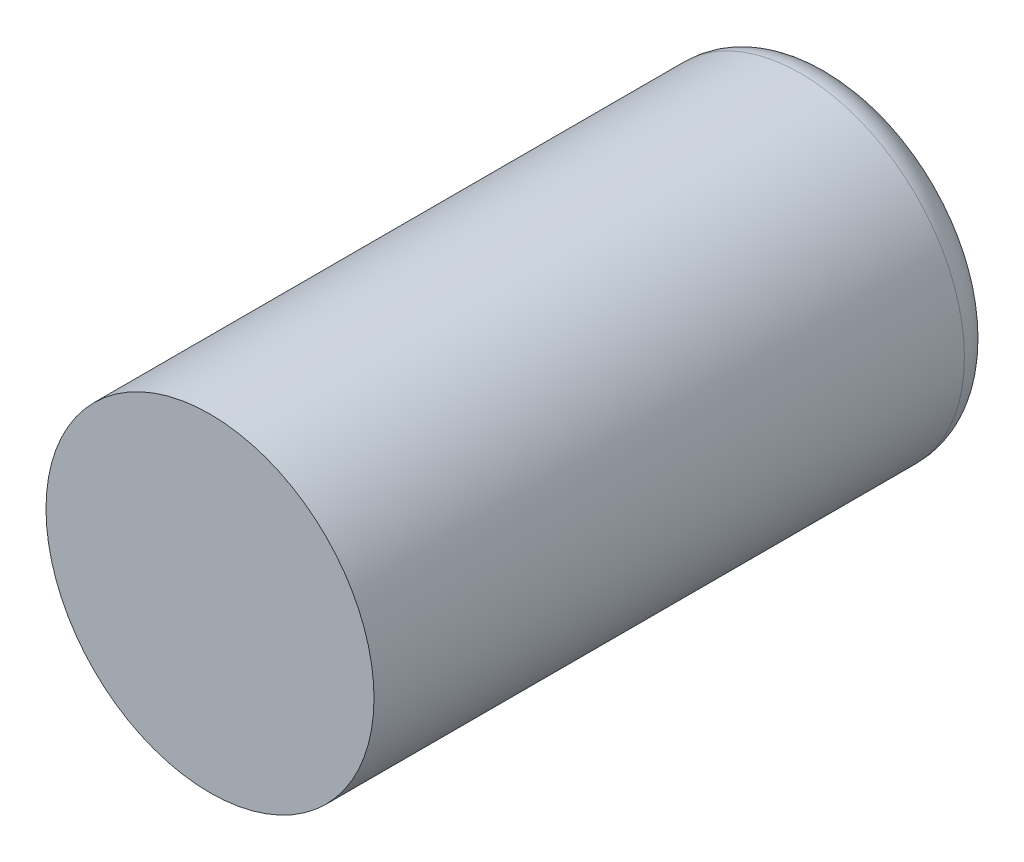
SolidWorks part; units mm, degrees
ref_plane "Ebene vorne" through (0, 0, 0) normal (0, 0, 1) x (1, 0, 0)
ref_plane "Ebene oben" through (0, 0, 0) normal (0, 1, 0) x (1, 0, 0)
ref_plane "Ebene rechts" through (0, 0, 0) normal (1, 0, 0) x (0, 0, -1)
sketch "Skizze1" plane through (0, 0, 0) normal (0, 0, 1) x (1, 0, 0)
  circle A0 centre (0, 0) radius 5
  dimension "D1" = 10
extrude "Aufsatz-Linear austragen1" add sketch "Skizze1" along normal blind 19 contours A0
fillet "Verrundung1" radius 1 1 edges at (5, 0, 0)
